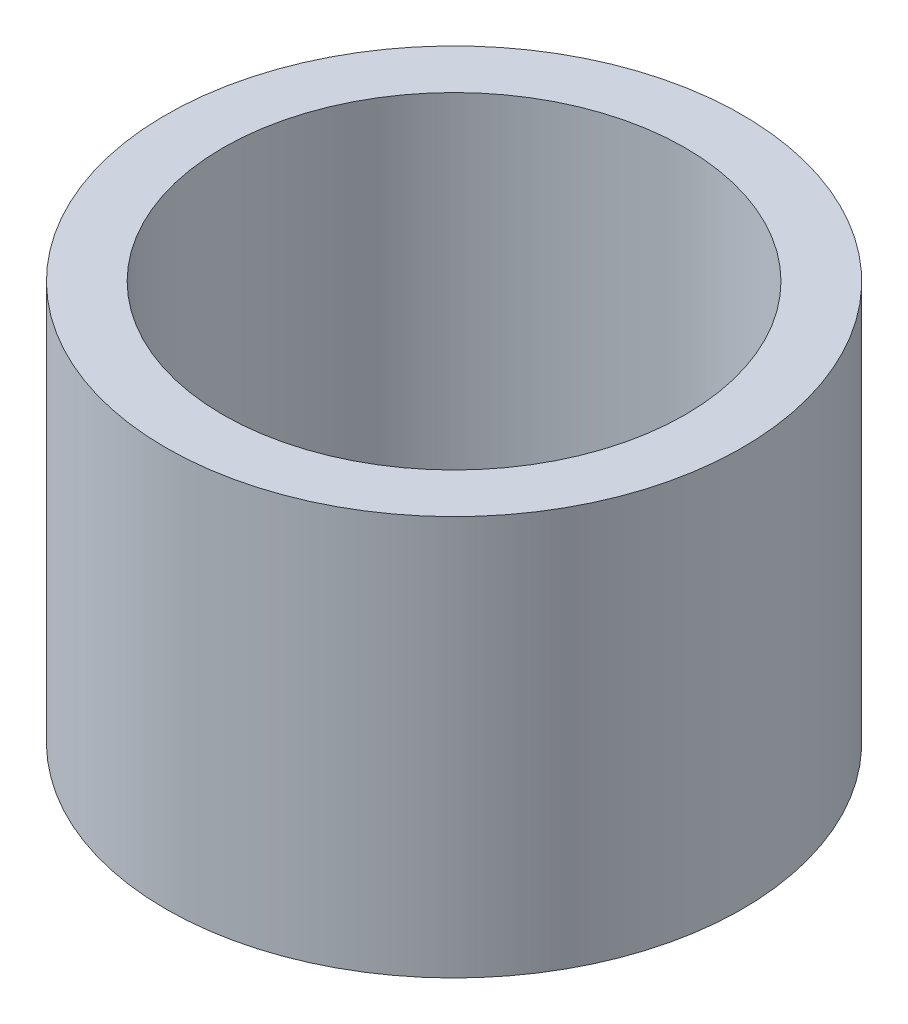
SolidWorks part; units mm, degrees
ref_plane "Front Plane" through (0, 0, 0) normal (0, 0, 1) x (1, 0, 0)
ref_plane "Top Plane" through (0, 0, 0) normal (0, 1, 0) x (1, 0, 0)
ref_plane "Right Plane" through (0, 0, 0) normal (1, 0, 0) x (0, 0, -1)
sketch "Sketch1" plane through (0, 0, 0) normal (0, 1, 0) x (1, 0, 0)
  circle A0 centre (0, 0) radius 4.05
  circle A1 centre (0, 0) radius 5.05
  dimension "D1" = 8.1
  dimension "D2" = 1
extrude "Boss-Extrude1" add sketch "Sketch1" along normal blind 7
